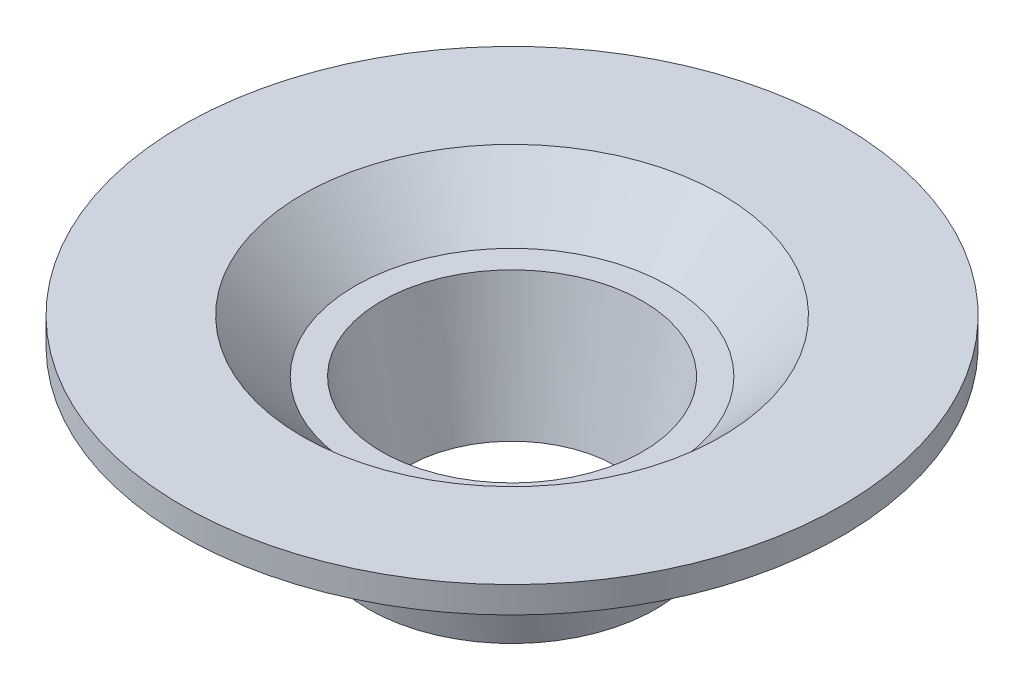
SolidWorks part; units mm, degrees
ref_plane "Front Plane" through (0, 0, 0) normal (0, 0, 1) x (1, 0, 0)
ref_plane "Top Plane" through (0, 0, 0) normal (0, 1, 0) x (1, 0, 0)
ref_plane "Right Plane" through (0, 0, 0) normal (1, 0, 0) x (0, 0, -1)
sketch "Sketch1" plane through (0, 0, 0) normal (0, 0, 1) x (1, 0, 0)
  line L0 (3.95, -4.9221) -> (0, -4.9221) construction
  line L1 (4.95, 0) -> (5.95, 0)
  line L2 (5.95, 0) -> (7.95, 2)
  line L3 (7.95, 2) -> (12.5, 2)
  line L4 (12.5, 2) -> (12.5, 1)
  line L5 (12.5, 1) -> (10.5, 1)
  line L6 (10.5, 1) -> (8.5779, -0.9221)
  line L16 (4.95, 0) -> (3.95, -4.9221)
  line L17 (3.95, -4.9221) -> (5.45, -4.9221)
  line L18 (0, -4.9221) -> (0, 0) construction
  line L19 (8.5779, -0.9221) -> (6.25, -0.9221)
  line L20 (6.25, -0.9221) -> (5.45, -4.9221)
  dimension "D1" = 7.9
  dimension "D2" = 1.5
  dimension "D3" = 9.9
  dimension "D4" = 2
  dimension "D5" = 135
  dimension "D6" = 1
  dimension "D7" = 2
  dimension "D8" = 4
  dimension "D9" = 1
  dimension "D10" = 25
  dimension "D11" = 12.5
revolve "Revolve1" add sketch "Sketch1" angle 360 about L18
